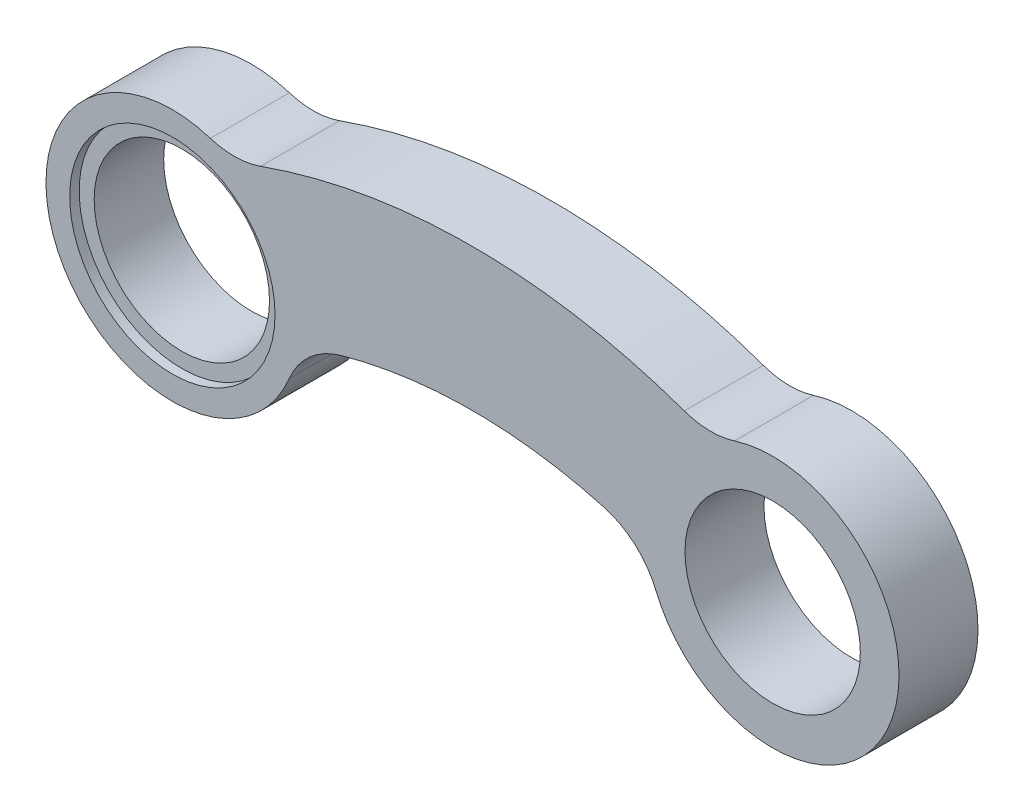
SolidWorks part; units mm, degrees
ref_plane "前视基准面" through (0, 0, 0) normal (0, 0, 1) x (1, 0, 0)
ref_plane "上视基准面" through (0, 0, 0) normal (0, 1, 0) x (1, 0, 0)
ref_plane "右视基准面" through (0, 0, 0) normal (1, 0, 0) x (0, 0, -1)
other "Configuration Table"
sketch "草图1" plane through (0, 0, 0) normal (0, 0, 1) x (1, 0, 0)
  line L0 (-38, 0) -> (0, 0) construction
  arc A0 (-7.9317, -1.0433) -> (-3.8424, 7.0168) centre (0, 0) ccw
  arc A1 (-34.1576, 7.0168) -> (-30.0683, -1.0433) centre (-38, 0) ccw
  arc A5 (-7.9317, -1.0433) -> (-30.0683, -1.0433) centre (-19, -30) ccw
  arc A6 (-3.8424, 7.0168) -> (-34.1576, 7.0168) centre (-19, -30) ccw
  point P10 (-19, 0)
  dimension "D1" = 8
  dimension "D2" = 8
  dimension "D3" = 40
  dimension "D4" = 31
  dimension "D5" = 38
  dimension "D6" = 30
extrude "凸台-拉伸1" add sketch "草图1" against normal blind 5
sketch "草图3" plane through (0, 0, -5) normal (0, 0, -1) x (-1, 0, 0)
  circle A0 centre (0, 0) radius 5.55
  circle A1 centre (38, 0) radius 5.55
extrude "切除-拉伸1" cut sketch "草图3" against normal up to surface (5 mm away) up to face at (-19, 0.9402, 0)
fillet "圆角1" radius 5 4 edges at (-3.8424, 7.0168, -2.5) (-34.1576, 7.0168, -2.5) (-7.9317, -1.0433, -2.5) (-30.0683, -1.0433, -2.5)
sketch "草图4" plane through (0, 0, 0) normal (0, 0, 1) x (1, 0, 0)
  circle A0 centre (-38, 0) radius 6.5
extrude "切除-拉伸2" cut sketch "草图4" against normal blind 0.6
